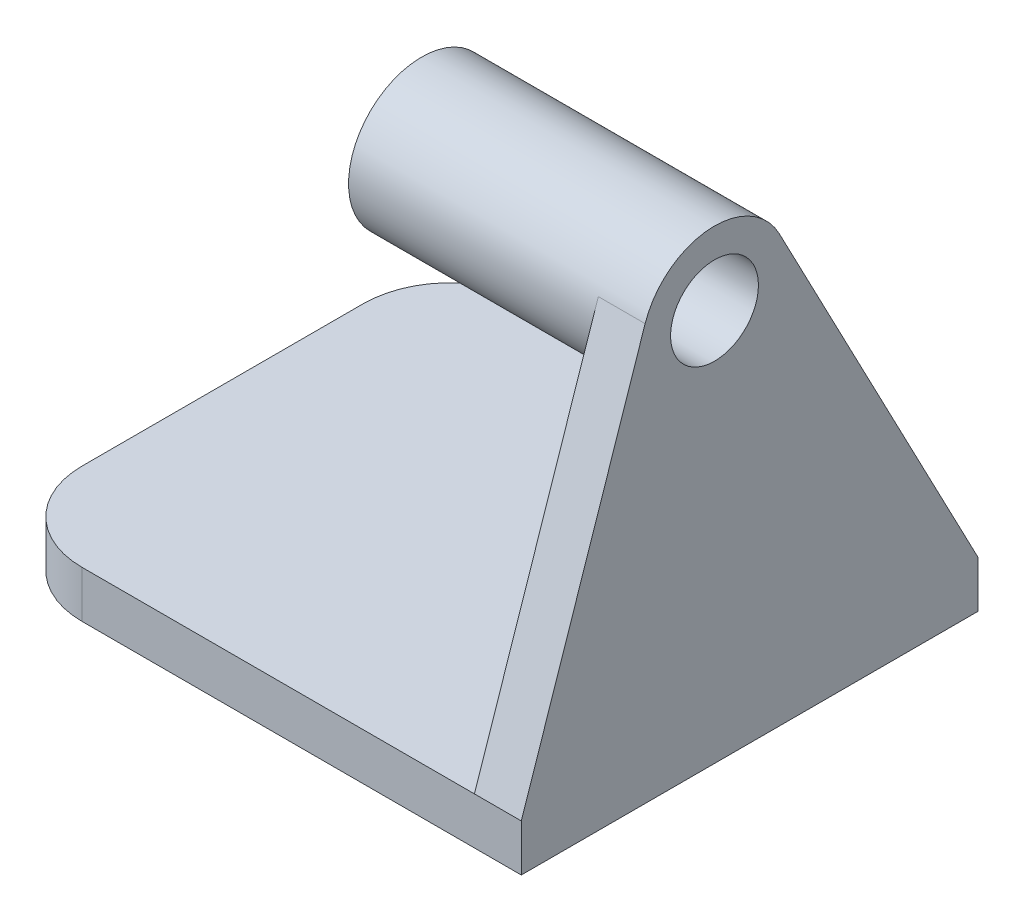
SolidWorks part; units mm, degrees
ref_plane "Front Plane" through (0, 0, 0) normal (0, 0, 1) x (1, 0, 0)
ref_plane "Top Plane" through (0, 0, 0) normal (0, 1, 0) x (1, 0, 0)
ref_plane "Right Plane" through (0, 0, 0) normal (1, 0, 0) x (0, 0, -1)
sketch "Sketch2" plane through (0, 0, 0) normal (0, 1, 0) x (1, 0, 0)
  line L1 (0, 78) -> (90, 78)
  line L2 (0, 78) -> (0, 0)
  line L3 (0, 0) -> (90, 0)
  line L4 (90, 78) -> (90, 0)
  dimension "D1" = 78
  dimension "D2" = 90
extrude "Boss-Extrude1" add sketch "Sketch2" along normal blind 8
ref_plane "Plane1" through (90, 0, 0) normal (1, 0, 0) x (0, 0, -1)
sketch "Sketch3" plane through (90, 0, 0) normal (1, 0, 0) x (0, 0, -1)
  line L0 (0, 8) -> (78, 8) construction
  line L4 (78, 8) -> (78, 0) construction
  circle A0 centre (33, 67) radius 12.5
  circle A1 centre (33, 67) radius 7.5
  point P7 (78, 4.7016)
  dimension "D1" = 25
  dimension "D2" = 15
  dimension "D3" = 59
  dimension "D4" = 45
extrude "Boss-Extrude2" add sketch "Sketch3" against normal blind 50 separate body
sketch "Sketch4" plane through (90, 0, 0) normal (1, 0, 0) x (0, 0, -1)
  line L0 (44.074, 72.798) -> (78, 8)
  line L1 (0, 8) -> (21.1504, 70.9795)
  line L6 (0, 0) -> (78, 0)
  line L7 (78, 0) -> (78, 8)
  line L8 (78, 8) -> (0, 8)
  line L9 (0, 8) -> (0, 0)
  line L12 (78, 8) -> (0, 8)
  circle A0 centre (33, 67) radius 12.5 construction
  arc A1 (21.1504, 70.9795) -> (44.074, 72.798) centre (33, 67) ccw
  dimension "D1" = 0
extrude "Boss-Extrude3" add sketch "Sketch4" against normal blind 8
fillet "Fillet1" radius 15 1 edges at (0, 4, 0)
fillet "Fillet2" radius 15 1 edges at (0, 4, -78)
